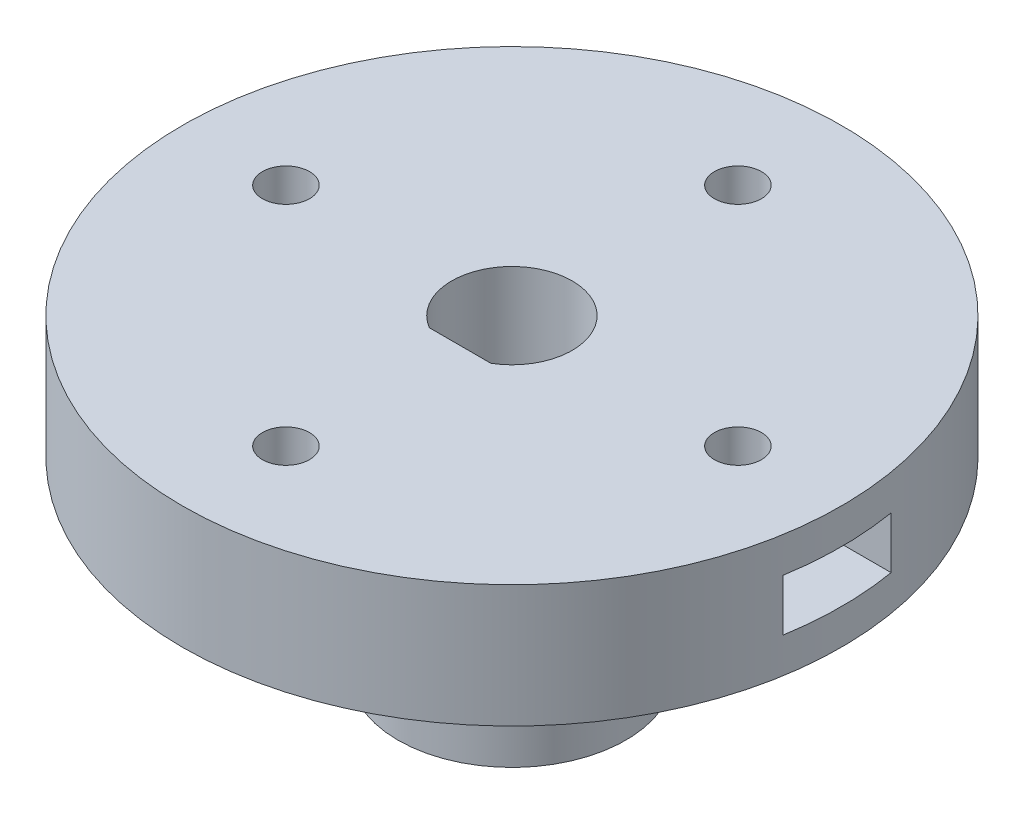
SolidWorks part; units mm, degrees
ref_plane "Front Plane" through (0, 0, 0) normal (0, 0, 1) x (1, 0, 0)
ref_plane "Top Plane" through (0, 0, 0) normal (0, 1, 0) x (1, 0, 0)
ref_plane "Right Plane" through (0, 0, 0) normal (1, 0, 0) x (0, 0, -1)
sketch "Sketch1" plane through (0, 0, 0) normal (0, 1, 0) x (1, 0, 0)
  circle A0 centre (0, 0) radius 3.05
  circle A1 centre (0, 0) radius 6.05
  dimension "D1" = 6.1
  dimension "D2" = 3
extrude "Boss-Extrude1" add sketch "Sketch1" along normal blind 10
sketch "Sketch2" plane through (0, 10, 0) normal (0, 1, 0) x (1, 0, 0)
  circle A0 centre (0, 0) radius 17.5
  dimension "D1" = 35
extrude "Boss-Extrude2" add sketch "Sketch2" along normal blind 6.5
sketch "Sketch3" plane through (0, 10, 0) normal (0, -1, 0) x (1, 0, 0)
  circle A0 centre (12, 0) radius 1.25
  circle A1 centre (0, -12) radius 1.25
  circle A2 centre (-12, 0) radius 1.25
  circle A3 centre (0, 12) radius 1.25
  point P11 (0, 0)
  dimension "D1" = 2.5
  dimension "D3" = 12
  dimension "D2" = 4
extrude "Cut-Extrude1" cut sketch "Sketch3" against normal up to next
sketch "Sketch4" plane through (0, 0, 0) normal (0, 0, 1) x (1, 0, 0)
  circle A0 centre (0, 4.9164) radius 1.5
  dimension "D1" = 3
extrude "Cut-Extrude2" cut sketch "Sketch4" against normal through all both and the other way through all
sketch "Sketch6" plane through (0, 10, 0) normal (0, -1, 0) x (-1, 0, 0)
  circle A0 centre (0, 0) radius 3.2
  dimension "D1" = 6.4
extrude "Cut-Extrude3" cut sketch "Sketch6" against normal up to next and the other way up to next
sketch "Sketch7" plane through (0, 0, 0) normal (0, -1, 0) x (1, 0, 0)
  line L1 (-1.6363, 2.75) -> (1.6363, 2.75)
  circle A2 centre (0, 0) radius 3.2 construction
  arc A3 (-1.6363, 2.75) -> (1.6363, 2.75) centre (0, 0) cw
  point P5 (0, 3.2)
  dimension "D1" = 0.45
extrude "Boss-Extrude3" add sketch "Sketch7" against normal up to surface (16.5 mm away) up to face at (0, 16.5, 3.2)
ref_plane "Plane1" through (17.5, 0, 0) normal (1, 0, 0) x (0, 0, -1)
sketch "Sketch8" plane through (17.5, 0, 0) normal (1, 0, 0) x (0, 0, -1)
  line L1 (-2.875, 11.875) -> (2.875, 11.875)
  line L2 (-2.875, 11.875) -> (-2.875, 14.625)
  line L3 (-2.875, 14.625) -> (2.875, 14.625)
  line L4 (2.875, 11.875) -> (2.875, 14.625)
  line L5 (-2.875, 11.875) -> (2.875, 14.625) construction
  line L6 (-2.875, 14.625) -> (2.875, 11.875) construction
  point P0 (0, 13.25)
  dimension "D1" = 5.75
  dimension "D2" = 0
  dimension "D3" = 2.75
extrude "Cut-Extrude4" cut sketch "Sketch8" against normal blind 5
sketch "Sketch9" plane through (0, 14.625, 0) normal (0, -1, 0) x (1, 0, 0)
  line L1 (15.3198, 0) -> (13.6599, 2.875)
  line L2 (13.6599, 2.875) -> (10.3401, 2.875)
  line L3 (10.3401, 2.875) -> (8.6802, 0)
  line L4 (8.6802, 0) -> (10.3401, -2.875)
  line L5 (10.3401, -2.875) -> (13.6599, -2.875)
  line L6 (13.6599, -2.875) -> (15.3198, 0)
  circle A0 centre (12, 0) radius 2.875 construction
  dimension "D1" = 5.75
extrude "Cut-Extrude5" cut sketch "Sketch9" along normal up to surface (2.75 mm away) up to face at (14.252, 11.875, 0)
mirror "Mirror1" about plane through (0, 0, 0) normal (1, 0, 0) of "Cut-Extrude4", "Cut-Extrude5"
